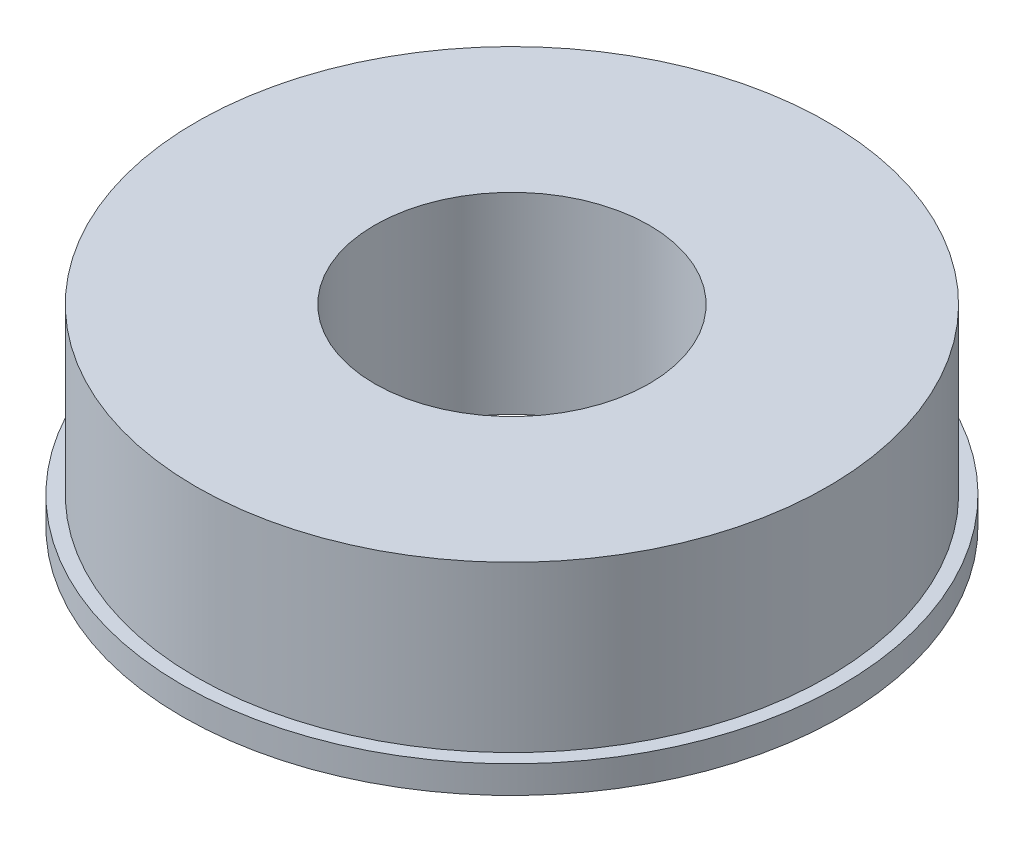
SolidWorks part; units mm, degrees
ref_plane "Front Plane" through (0, 0, 0) normal (0, 0, 1) x (1, 0, 0)
ref_plane "Top Plane" through (0, 0, 0) normal (0, 1, 0) x (1, 0, 0)
ref_plane "Right Plane" through (0, 0, 0) normal (1, 0, 0) x (0, 0, -1)
sketch "Sketch1" plane through (0, 0, 0) normal (0, 1, 0) x (1, 0, 0)
  circle A0 centre (0, 0) radius 12
  dimension "D1" = 24
extrude "Boss-Extrude1" add sketch "Sketch1" along normal blind 7
sketch "Sketch2" plane through (0, 7, 0) normal (0, 1, 0) x (1, 0, 0)
  circle A0 centre (0, 0) radius 11.5
  dimension "D1" = 23
extrude "Cut-Extrude3" cut sketch "Sketch2" against normal blind 6 flip side to cut
sketch "Sketch3" plane through (0, 7, 0) normal (0, 1, 0) x (1, 0, 0)
  circle A0 centre (0, 0) radius 5
extrude "Cut-Extrude4" cut sketch "Sketch3" against normal up to next
